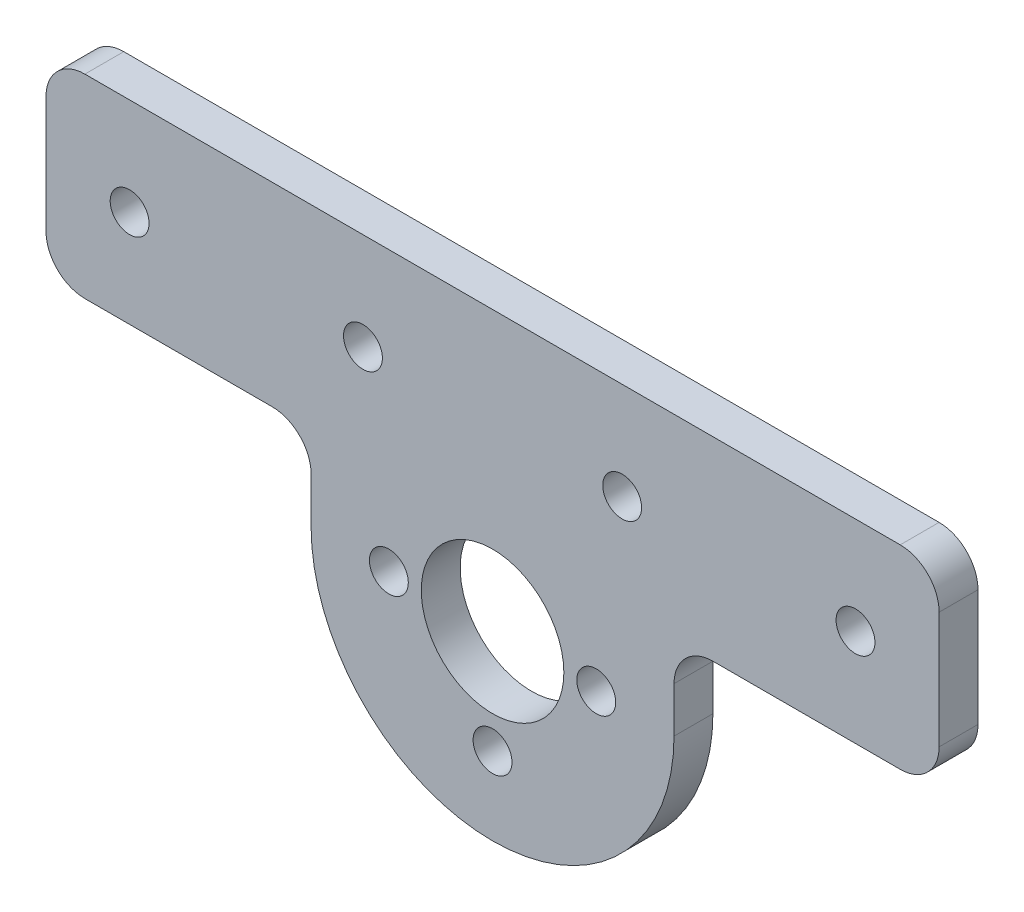
SolidWorks part; units mm, degrees
ref_plane "前视基准面" through (0, 0, 0) normal (0, 0, 1) x (1, 0, 0)
ref_plane "上视基准面" through (0, 0, 0) normal (0, 1, 0) x (1, 0, 0)
ref_plane "右视基准面" through (0, 0, 0) normal (1, 0, 0) x (0, 0, -1)
other "Configuration Table"
sketch "草图1" plane through (0, 0, 0) normal (0, 0, 1) x (1, 0, 0)
  line L0 (0, 0) -> (0, 14.9098) construction
  line L1 (0, 0) -> (25.3565, 0) construction
  line L2 (-14, 0) -> (-14, 27.2875)
  line L3 (-14, 27.2875) -> (14, 27.2875)
  line L4 (14, 27.2875) -> (14, 0)
  circle A0 centre (0, 0) radius 14
  circle A1 centre (-8, 0) radius 1.5
  circle A2 centre (8, 0) radius 1.5
  circle A3 centre (0, -8) radius 1.5
  dimension "D2" = 28
  dimension "D4" = 3
  dimension "D1" = 16
  dimension "D3" = 8
extrude "凸台-拉伸1" add sketch "草图1" along normal blind 3 contours A0 L4 L3 L2 | A0 A3 A2 A1
sketch "草图2" plane through (0, 0, 3) normal (0, 0, 1) x (1, 0, 0)
  circle A0 centre (0, 0) radius 5.5
  dimension "D1" = 11
extrude "切除-拉伸1" cut sketch "草图2" against normal blind 11
sketch "草图3" plane through (0, 0, 3) normal (0, 0, 1) x (1, 0, 0)
  line L0 (14, 27.2875) -> (22.0404, 27.2875)
  line L1 (22.0404, 27.2875) -> (22.0404, 21.5075)
  line L2 (22.0404, 21.5075) -> (-23.5232, 21.5075)
  line L3 (-23.5232, 21.5075) -> (-23.5232, 27.2875)
  line L4 (-23.5232, 27.2875) -> (14, 27.2875)
  dimension "D1" = 5.78
extrude "切除-拉伸2" cut sketch "草图3" against normal blind 11
sketch "草图4" plane through (0, 0, 3) normal (0, 0, 1) x (1, 0, 0)
  line L0 (14, 21.5075) -> (34.451, 21.5075)
  line L1 (34.451, 21.5075) -> (34.451, 6.5075)
  line L2 (34.451, 6.5075) -> (14, 6.5075)
  line L3 (14, 21.5075) -> (14, 0) construction
  line L4 (0, 0) -> (0, 29.903) construction
  line L5 (34.451, 14.0075) -> (-23.0028, 14.0075) construction
  line L6 (-34.451, 14.0075) -> (23.0028, 14.0075) construction
  line L7 (-34.451, 6.5075) -> (-14, 6.5075)
  line L8 (-34.451, 21.5075) -> (-34.451, 6.5075)
  line L9 (-14, 21.5075) -> (-34.451, 21.5075)
  line L10 (-14, 6.5075) -> (14, 6.5075)
  line L11 (-14, 21.5075) -> (14, 21.5075)
  circle A0 centre (10, 14.0075) radius 1.5
  circle A1 centre (28, 14.0075) radius 1.5
  circle A2 centre (-10, 14.0075) radius 1.5
  circle A3 centre (-28, 14.0075) radius 1.5
  dimension "D4" = 3
  dimension "D5" = 3
  dimension "D1" = 15
  dimension "D2" = 20
  dimension "D3" = 28
sketch "草图6" plane through (0, 0, 3) normal (0, 0, 1) x (1, 0, 0)
  circle A0 centre (10, 14.0075) radius 1.5 construction
  circle A3 centre (-10, 14.0075) radius 1.5 construction
  circle A4 centre (10, 14.0075) radius 1.5
  circle A5 centre (-10, 14.0075) radius 1.5
extrude "切除-拉伸3" cut sketch "草图6" against normal blind 11
extrude "凸台-拉伸2" add sketch "草图4" against normal blind 3
fillet "圆角1" radius 3 6 edges at (-34.451, 21.5075, 1.5) (34.451, 21.5075, 1.5) (34.451, 6.5075, 1.5) (-34.451, 6.5075, 1.5) (-14, 6.5075, 1.5) (14, 6.5075, 1.5)
